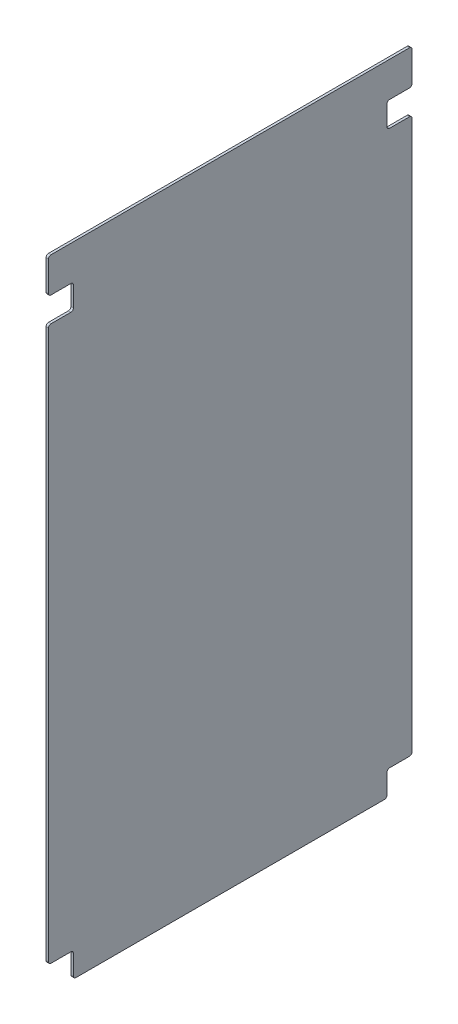
SolidWorks part; units mm, degrees
material "Acrylic (Medium-high impact)"
ref_plane "Front Plane" through (0, 0, 0) normal (0, 0, 1) x (1, 0, 0)
ref_plane "Top Plane" through (0, 0, 0) normal (0, 1, 0) x (1, 0, 0)
ref_plane "Right Plane" through (0, 0, 0) normal (1, 0, 0) x (0, 0, -1)
sketch "Sketch1" plane through (0, 0, 0) normal (1, 0, 0) x (0, 0, -1)
  line L1 (0, 0) -> (463.55, 0)
  line L2 (0, 0) -> (0, 814.3875)
  line L3 (0, 814.3875) -> (463.55, 814.3875)
  line L4 (463.55, 0) -> (463.55, 814.3875)
  dimension "D1" = 814.3875
  dimension "D2" = 463.55
extrude "Boss-Extrude1" add sketch "Sketch1" along normal blind 3.175
fillet "Fillet1" radius 3.175 4 edges at (1.5875, 0, -463.55) (1.5875, 0, 0) (1.5875, 814.3875, -463.55) (1.5875, 814.3875, 0)
sketch "Sketch3" plane through (3.175, 0, 0) normal (1, 0, 0) x (0, 0, -1)
  line L0 (0, 811.2125) -> (0, 3.175) construction
  line L1 (0, 769.9375) -> (31.75, 769.9375)
  line L2 (0, 769.9375) -> (0, 738.1875)
  line L3 (0, 738.1875) -> (31.75, 738.1875)
  line L4 (31.75, 769.9375) -> (31.75, 738.1875)
  line L5 (460.375, 814.3875) -> (3.175, 814.3875) construction
  line L6 (231.775, 814.3875) -> (231.775, 718.9831) construction
  line L7 (431.8, 769.9375) -> (431.8, 738.1875)
  line L8 (463.55, 738.1875) -> (431.8, 738.1875)
  line L9 (463.55, 769.9375) -> (463.55, 738.1875)
  line L10 (463.55, 769.9375) -> (431.8, 769.9375)
  line L11 (431.8, 0) -> (431.8, 31.75)
  line L12 (0, 0) -> (31.75, 0)
  line L13 (0, 0) -> (0, 31.75)
  line L14 (0, 31.75) -> (31.75, 31.75)
  line L15 (31.75, 0) -> (31.75, 31.75)
  line L16 (463.55, 31.75) -> (431.8, 31.75)
  line L17 (463.55, 0) -> (463.55, 31.75)
  line L18 (463.55, 0) -> (431.8, 0)
  dimension "D1" = 31.75
  dimension "D2" = 31.75
  dimension "D3" = 44.45
  dimension "D4" = 31.75
  dimension "D5" = 31.75
extrude "Cut-Extrude2" cut sketch "Sketch3" against normal up to next
fillet "Fillet2" radius 3.175 4 edges at (1.5875, 738.1875, -31.75) (1.5875, 738.1875, 0) (1.5875, 769.9375, -31.75) (1.5875, 769.9375, 0)
fillet "Fillet3" radius 3.175 4 edges at (1.5875, 769.9375, -431.8) (1.5875, 738.1875, -431.8) (1.5875, 738.1875, -463.55) (1.5875, 769.9375, -463.55)
fillet "Fillet4" radius 3.175 6 edges at (1.5875, 31.75, -463.55) (1.5875, 31.75, -431.8) (1.5875, 0, -431.8) (1.5875, 31.75, 0) (1.5875, 31.75, -31.75) (1.5875, 0, -31.75)
